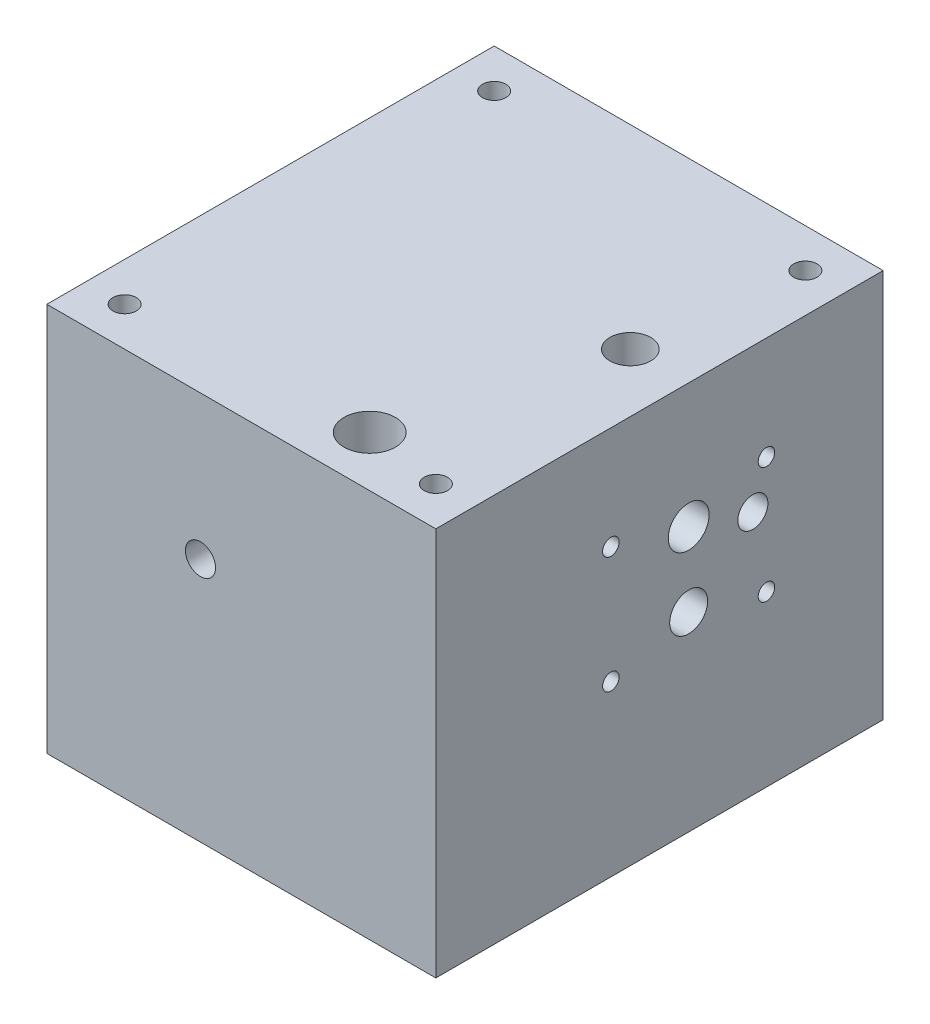
SolidWorks part; units mm, degrees
ref_plane "前视基准面" through (0, 0, 0) normal (0, 0, 1) x (1, 0, 0)
ref_plane "上视基准面" through (0, 0, 0) normal (0, 1, 0) x (1, 0, 0)
ref_plane "右视基准面" through (0, 0, 0) normal (1, 0, 0) x (0, 0, -1)
sketch "草图1" plane through (0, 0, 0) normal (0, 1, 0) x (1, 0, 0)
  line L1 (100, -100) -> (-100, -100)
  line L2 (100, -100) -> (100, 100)
  line L3 (100, 100) -> (-100, 100)
  line L4 (-100, -100) -> (-100, 100)
  line L5 (100, -100) -> (-100, 100) construction
  line L6 (100, 100) -> (-100, -100) construction
  point P0 (0, 0)
  dimension "D1" = 200
  dimension "D2" = 200
extrude "凸台-拉伸1" add sketch "草图1" along normal blind 200
sketch "草图9" plane through (100, 0, 0) normal (1, 0, 0) x (0, 0, -1)
  line L0 (0, 117) -> (0, 19.4773) construction
  line L1 (51, 74) -> (-51, 74)
  line L2 (51, 74) -> (51, 160)
  line L3 (51, 160) -> (-51, 160)
  line L4 (-51, 74) -> (-51, 160)
  line L5 (51, 74) -> (-51, 160) construction
  line L6 (51, 160) -> (-51, 74) construction
  line L7 (100, 200) -> (100, 0) construction
  line L8 (0, 117) -> (-57.0715, 117) construction
  line L9 (-100, 200) -> (100, 200) construction
  circle A0 centre (0, 136) radius 16.5
  circle A1 centre (0, 136) radius 16.5
  circle A2 centre (33, 126) radius 10
  circle A3 centre (0, 98) radius 16.5
  point P0 (-40, 147)
  point P1 (0, 117)
  point P2 (0, 117)
  point P7 (0, 136)
  point P8 (-40, 87)
  point P11 (0, 136)
  point P12 (40, 147)
  point P13 (40, 87)
  point P23 (33, 126)
  dimension "D14" = 33
  dimension "D15" = 33
  dimension "D19" = 20
  dimension "D21" = 33
  dimension "D1" = 86
  dimension "D2" = 102
  dimension "D3" = 100
  dimension "D4" = 40
  dimension "D5" = 40
  dimension "D6" = 30
  dimension "D7" = 30
  dimension "D8" = 30
  dimension "D9" = 30
  dimension "D10" = 11
  dimension "D11" = 40
  dimension "D12" = 19
  dimension "D13" = 19
  dimension "D16" = 40
  dimension "D17" = 9
  dimension "D18" = 33
  dimension "D20" = 38
hole_wizard "M10 螺纹孔1" positions "草图10" profile "草图11" tap size "M10" standard "GB"
sketch "草图10" plane through (100, 0, 0) normal (1, 0, 0) x (0, 0, -1)
  point P0 (-40, 87)
  point P3 (-40, 147)
  point P6 (40, 147)
  point P9 (40, 87)
sketch "草图11" plane through (100, 87, 40) normal (0, 1, 0) x (0, 0, -1)
  line L0 (0, 0) -> (0, 19.5537)
  line L1 (0, 19.5537) -> (4.25, 17)
  line L2 (4.25, 17) -> (4.25, 0)
  line L5 (4.25, 0) -> (0, 0)
  line L10 (0, 19.5537) -> (-4.25, 17) construction
  line L11 (0, -6.35) -> (0, 107.95) construction
  dimension "螺纹孔钻头直径" = 8.5
  dimension "螺纹孔钻头深度" = 17
  dimension "导头角度" = 118
cosmetic thread "孔螺蚊线5" parameters "D1"=17, "D2"=10
cosmetic thread "孔螺蚊线6" parameters "D1"=17, "D2"=10
cosmetic thread "孔螺蚊线7" parameters "D1"=17, "D2"=10
cosmetic thread "孔螺蚊线8" parameters "D1"=17, "D2"=10
sketch "草图12" plane through (0, 0, -100) normal (0, 0, -1) x (-1, 0, 0)
  line L0 (-100, 200) -> (-100, 0) construction
  line L1 (173, 43.5) -> (-173, 43.5)
  line L2 (173, 43.5) -> (173, 116.5)
  line L3 (173, 116.5) -> (-173, 116.5)
  line L4 (-173, 43.5) -> (-173, 116.5)
  line L5 (173, 43.5) -> (-173, 116.5) construction
  line L6 (173, 116.5) -> (-173, 43.5) construction
  line L7 (-68, 116.5) -> (-68, 43.5)
  line L8 (68, 116.5) -> (68, 43.5)
  line L9 (-100, 200) -> (100, 200) construction
  circle A0 centre (0, 62) radius 12.5
  circle A1 centre (0, 62) radius 9
  circle A2 centre (-21, 98) radius 9
  circle A3 centre (-21, 98) radius 12.5
  circle A4 centre (21, 98) radius 9
  circle A5 centre (21, 98) radius 12.5
  circle A6 centre (42, 62) radius 9
  circle A7 centre (42, 62) radius 12.5
  point P0 (0, 80)
  point P11 (44, 107)
  point P12 (21, 53)
  point P13 (-44, 107)
  point P14 (-21, 53)
  point P17 (0, 62)
  point P19 (-21, 98)
  point P22 (21, 98)
  point P31 (42, 62)
  dimension "D16" = 18
  dimension "D17" = 25
  dimension "D22" = 25
  dimension "D23" = 18
  dimension "D24" = 18
  dimension "D25" = 25
  dimension "D27" = 18
  dimension "D28" = 25
  dimension "D1" = 346
  dimension "D2" = 100
  dimension "D3" = 68
  dimension "D4" = 68
  dimension "D5" = 27
  dimension "D6" = 27
  dimension "D7" = 27
  dimension "D8" = 27
  dimension "D9" = 73
  dimension "D10" = 21
  dimension "D11" = 21
  dimension "D12" = 44
  dimension "D13" = 44
  dimension "D14" = 156.5
  dimension "D15" = 18
  dimension "D18" = 18
  dimension "D19" = 18
  dimension "D20" = 21
  dimension "D21" = 21
  dimension "D26" = 42
  dimension "D29" = 138
hole_wizard "M8 螺纹孔1" positions "草图13" profile "草图14" tap size "M8" standard "GB"
sketch "草图13" plane through (0, 0, -100) normal (0, 0, -1) x (-1, 0, 0)
  point P0 (-44, 107)
  point P3 (-21, 53)
  point P6 (21, 53)
  point P9 (44, 107)
sketch "草图14" plane through (44, 107, -100) normal (1, 0, 0) x (0, 1, 0)
  line L0 (0, 0) -> (0, 27.0429)
  line L1 (0, 27.0429) -> (3.4, 25)
  line L2 (3.4, 25) -> (3.4, 0)
  line L5 (3.4, 0) -> (0, 0)
  line L10 (0, 27.0429) -> (-3.4, 25) construction
  line L11 (0, -6.35) -> (0, 107.95) construction
  dimension "螺纹孔钻头直径" = 6.8
  dimension "螺纹孔钻头深度" = 25
  dimension "导头角度" = 118
cosmetic thread "孔螺蚊线9" parameters "D1"=16, "D2"=8
cosmetic thread "孔螺蚊线10" parameters "D1"=16, "D2"=8
cosmetic thread "孔螺蚊线11" parameters "D1"=16, "D2"=8
cosmetic thread "孔螺蚊线12" parameters "D1"=16, "D2"=8
sketch "草图16" plane through (-100, 0, 0) normal (-1, 0, 0) x (0, 0, 1)
  line L0 (-67.5744, 98.0404) -> (-50, 98.0404) construction
  line L5 (-50, 138) -> (56, 138)
  line L6 (-50, 138) -> (-50, 58)
  line L7 (-50, 58) -> (56, 58)
  line L8 (56, 138) -> (56, 58)
  line L9 (56, 98.0404) -> (97.1803, 98.0404) construction
  line L11 (-100, 200) -> (100, 200) construction
  circle A0 centre (0, 98.0404) radius 6
  circle A1 centre (0, 98.0404) radius 10
  circle A2 centre (-25, 98) radius 6
  circle A3 centre (-25, 98) radius 10
  point P4 (0, 98.0404)
  point P7 (23, 71.0404)
  point P8 (23, 125.0404)
  point P9 (-31, 125.0404)
  point P10 (-31, 71.0404)
  point P18 (-25, 98)
  dimension "D13" = 20
  dimension "D14" = 12
  dimension "D17" = 20
  dimension "D18" = 12
  dimension "D1" = 106
  dimension "D2" = 80
  dimension "D3" = 56
  dimension "D4" = 27
  dimension "D5" = 27
  dimension "D6" = 27
  dimension "D7" = 27
  dimension "D8" = 23
  dimension "D9" = 23
  dimension "D10" = 54
  dimension "D11" = 54
  dimension "D12" = 62
  dimension "D15" = 40
  dimension "D16" = 48
  dimension "D19" = 75
hole_wizard "M14 螺纹孔2" positions "草图19" profile "草图18" tap size "M14" standard "IS"
sketch "草图19" plane through (-100, 0, 0) normal (-1, 0, 0) x (0, 0, 1)
  point P0 (23, 125.0404)
  point P3 (-31, 125.0404)
  point P6 (-31, 71.0404)
  point P9 (23, 71.0404)
sketch "草图18" plane through (-100, 125.0404, 23) normal (0, 1, 0) x (0, 0, 1)
  line L0 (0, 0) -> (0, 20.6052)
  line L1 (0, 20.6052) -> (6, 17)
  line L2 (6, 17) -> (6, 0)
  line L5 (6, 0) -> (0, 0)
  line L10 (0, 20.6052) -> (-6, 17) construction
  line L11 (0, -6.35) -> (0, 107.95) construction
  dimension "螺纹孔钻头直径" = 12
  dimension "螺纹孔钻头深度" = 17
  dimension "导头角度" = 118
cosmetic thread "孔螺蚊线13" parameters "D1"=17, "D2"=14
cosmetic thread "孔螺蚊线14" parameters "D1"=17, "D2"=14
cosmetic thread "孔螺蚊线15" parameters "D1"=17, "D2"=14
cosmetic thread "孔螺蚊线16" parameters "D1"=17, "D2"=14
sketch "草图22" plane through (0, 200, 0) normal (0, 1, 0) x (1, 0, 0)
  line L0 (100, -100) -> (100, 100) construction
  line L1 (-173, 100) -> (173, 100) construction
  point P0 (70, 0)
  dimension "D1" = 30
  dimension "D2" = 100
hole_wizard "M24 螺纹孔的螺纹孔钻头1" positions "草图25" profile "草图26" hole size "M24" standard "IS"
sketch "草图25" plane through (0, 200, 0) normal (0, 1, 0) x (1, 0, 0)
  point P0 (70, 0)
sketch "草图26" plane through (70, 200, 0) normal (1, 0, 0) x (0, 0, 1)
  line L0 (0, 0) -> (0, 66.309)
  line L1 (0, 66.309) -> (10.5, 60)
  line L2 (10.5, 60) -> (10.5, 0)
  line L5 (10.5, 0) -> (0, 0)
  line L10 (0, 66.309) -> (-10.5, 60) construction
  line L11 (0, -6.35) -> (0, 107.95) construction
  dimension "孔直径" = 21
  dimension "孔深度" = 60
  dimension "导头角度" = 118
hole_wizard "M24 螺纹孔的螺纹孔钻头2" positions "草图29" profile "草图30" hole size "M24" standard "IS"
sketch "草图29" plane through (100, 0, 0) normal (1, 0, 0) x (0, 0, -1)
  point P0 (0, 136)
sketch "草图30" plane through (100, 136, 0) normal (0, 1, 0) x (0, 0, -1)
  line L0 (0, 0) -> (0, 48.309)
  line L1 (0, 48.309) -> (10.5, 42)
  line L2 (10.5, 42) -> (10.5, 0)
  line L5 (10.5, 0) -> (0, 0)
  line L10 (0, 48.309) -> (-10.5, 42) construction
  line L11 (0, -6.35) -> (0, 107.95) construction
  dimension "孔直径" = 21
  dimension "孔深度" = 42
  dimension "导头角度" = 118
hole_wizard "M22 螺纹孔的螺纹孔钻头1" positions "草图31" profile "草图32" hole size "M22" standard "IS"
sketch "草图31" plane through (0, 0, -100) normal (0, 0, -1) x (-1, 0, 0)
  point P0 (-21, 98)
sketch "草图32" plane through (21, 98, -100) normal (1, 0, 0) x (0, 1, 0)
  line L0 (0, 0) -> (0, 116.8584)
  line L1 (0, 116.8584) -> (9.75, 111)
  line L2 (9.75, 111) -> (9.75, 0)
  line L5 (9.75, 0) -> (0, 0)
  line L10 (0, 116.8584) -> (-9.75, 111) construction
  line L11 (0, -6.35) -> (0, 107.95) construction
  dimension "孔直径" = 19.5
  dimension "孔深度" = 111
  dimension "导头角度" = 118
hole_wizard "M22 螺纹孔的螺纹孔钻头3" positions "草图35" profile "草图36" hole size "M22" standard "IS"
sketch "草图35" plane through (-100, 0, 0) normal (-1, 0, 0) x (0, 0, 1)
  point P0 (-25, 98)
sketch "草图36" plane through (-100, 98, -25) normal (0, 1, 0) x (0, 0, 1)
  line L0 (0, 0) -> (0, 95.8584)
  line L1 (0, 95.8584) -> (9.75, 90)
  line L2 (9.75, 90) -> (9.75, 0)
  line L5 (9.75, 0) -> (0, 0)
  line L10 (0, 95.8584) -> (-9.75, 90) construction
  line L11 (0, -6.35) -> (0, 107.95) construction
  dimension "孔直径" = 19.5
  dimension "孔深度" = 90
  dimension "导头角度" = 118
hole_wizard "M22 螺纹孔的螺纹孔钻头4" positions "草图37" profile "草图38" hole size "M22" standard "IS"
sketch "草图37" plane through (0, 0, -100) normal (0, 0, -1) x (-1, 0, 0)
  point P0 (21, 98)
sketch "草图38" plane through (-21, 98, -100) normal (1, 0, 0) x (0, 1, 0)
  line L0 (0, 0) -> (0, 80.8584)
  line L1 (0, 80.8584) -> (9.75, 75)
  line L2 (9.75, 75) -> (9.75, 0)
  line L5 (9.75, 0) -> (0, 0)
  line L10 (0, 80.8584) -> (-9.75, 75) construction
  line L11 (0, -6.35) -> (0, 107.95) construction
  dimension "孔直径" = 19.5
  dimension "孔深度" = 75
  dimension "导头角度" = 118
hole_wizard "M18 螺纹孔的螺纹孔钻头1" positions "草图41" profile "草图42" hole size "M18" standard "GB"
sketch "草图41" plane through (-100, 0, 0) normal (-1, 0, 0) x (0, 0, 1)
  point P0 (0, 98.0404)
sketch "草图42" plane through (-100, 98.0404, 0) normal (0, 1, 0) x (0, 0, 1)
  line L0 (0, 0) -> (0, 92.6567)
  line L1 (0, 92.6567) -> (7.75, 88)
  line L2 (7.75, 88) -> (7.75, 0)
  line L5 (7.75, 0) -> (0, 0)
  line L10 (0, 92.6567) -> (-7.75, 88) construction
  line L11 (0, -6.35) -> (0, 107.95) construction
  dimension "孔直径" = 15.5
  dimension "孔深度" = 88
  dimension "导头角度" = 118
hole_wizard "M18 螺纹孔的螺纹孔钻头4" positions "草图48" profile "草图49" hole size "M18" standard "GB"
sketch "草图48" plane through (100, 0, 0) normal (1, 0, 0) x (0, 0, -1)
  point P0 (33, 126)
sketch "草图49" plane through (100, 126, -33) normal (0, 1, 0) x (0, 0, -1)
  line L0 (0, 0) -> (0, 134.6567)
  line L1 (0, 134.6567) -> (7.75, 130)
  line L2 (7.75, 130) -> (7.75, 0)
  line L5 (7.75, 0) -> (0, 0)
  line L10 (0, 134.6567) -> (-7.75, 130) construction
  line L11 (0, -6.35) -> (0, 107.95) construction
  dimension "孔直径" = 15.5
  dimension "孔深度" = 130
  dimension "导头角度" = 118
ref_plane "基准面2" through (0, 0, 0) normal (0, 0, 1) x (1, 0, 0)
sketch "草图50" plane through (0, 0, 0) normal (0, 0, 1) x (1, 0, 0)
  line L4 (-100, 0) -> (100, 0)
  line L5 (100, 0) -> (100, 200)
  line L6 (100, 200) -> (-100, 200)
  line L7 (-100, 200) -> (-100, 0)
  line L8 (-100, 0) -> (100, 0)
  line L9 (100, 0) -> (100, 200)
  line L10 (100, 200) -> (-100, 200)
  line L11 (-100, 200) -> (-100, 0)
  point P0 (-21, 126)
  dimension "D2" = 79
  dimension "D3" = 74
  dimension "D1" = 0
sketch "草图67" plane through (-100, 0, 0) normal (-1, 0, 0) x (0, 0, 1)
  line L0 (-100, 0) -> (100, 0) construction
  line L1 (19, 0) -> (-41, 0)
  line L2 (19, 0) -> (19, 53)
  line L3 (19, 53) -> (-41, 53)
  line L4 (-41, 0) -> (-41, 53)
  line L5 (-100, 200) -> (-100, 0) construction
  circle A0 centre (-25, 26.5) radius 5.5
  circle A1 centre (0, 26.5) radius 5.5
  point P6 (-9, 9)
  point P7 (-9, 44)
  point P8 (-29, 9)
  point P9 (-29, 44)
  point P10 (-25, 26.5)
  point P11 (0, 26.5)
  dimension "D14" = 11
  dimension "D15" = 11
  dimension "D1" = 60
  dimension "D2" = 53
  dimension "D3" = 12
  dimension "D4" = 32
  dimension "D5" = 12
  dimension "D6" = 32
  dimension "D7" = 9
  dimension "D8" = 9
  dimension "D9" = 9
  dimension "D10" = 9
  dimension "D11" = 26.5
  dimension "D12" = 16
  dimension "D13" = 100
  dimension "D16" = 75
hole_wizard "M22 螺纹孔的螺纹孔钻头5" positions "草图68" profile "草图69" hole size "M22" standard "GB"
sketch "草图68" plane through (100, 0, 0) normal (1, 0, 0) x (0, 0, -1)
  point P0 (0, 98)
sketch "草图69" plane through (100, 98, 0) normal (0, 1, 0) x (0, 0, -1)
  line L0 (0, 0) -> (0, 84.8584)
  line L1 (0, 84.8584) -> (9.75, 79)
  line L2 (9.75, 79) -> (9.75, 0)
  line L5 (9.75, 0) -> (0, 0)
  line L10 (0, 84.8584) -> (-9.75, 79) construction
  line L11 (0, -6.35) -> (0, 107.95) construction
  dimension "孔直径" = 19.5
  dimension "孔深度" = 79
  dimension "导头角度" = 118
hole_wizard "M10 螺纹孔2" positions "草图70" profile "草图71" tap size "M10" standard "GB"
sketch "草图70" plane through (-100, 0, 0) normal (-1, 0, 0) x (0, 0, 1)
  point P0 (-9, 44)
  point P3 (-29, 44)
  point P6 (-29, 9)
  point P9 (-9, 9)
sketch "草图71" plane through (-100, 44, -9) normal (0, 1, 0) x (0, 0, 1)
  line L0 (0, 0) -> (0, 12.5537)
  line L1 (0, 12.5537) -> (4.25, 10)
  line L2 (4.25, 10) -> (4.25, 0)
  line L5 (4.25, 0) -> (0, 0)
  line L10 (0, 12.5537) -> (-4.25, 10) construction
  line L11 (0, -6.35) -> (0, 107.95) construction
  dimension "螺纹孔钻头直径" = 8.5
  dimension "螺纹孔钻头深度" = 10
  dimension "导头角度" = 118
cosmetic thread "孔螺蚊线17" parameters "D1"=10, "D2"=10
cosmetic thread "孔螺蚊线18" parameters "D1"=10, "D2"=10
cosmetic thread "孔螺蚊线19" parameters "D1"=10, "D2"=10
cosmetic thread "孔螺蚊线20" parameters "D1"=10, "D2"=10
hole_wizard "M10 螺纹孔的螺纹孔钻头1" positions "草图72" profile "草图73" hole size "M10" standard "GB"
sketch "草图72" plane through (-100, 0, 0) normal (-1, 0, 0) x (0, 0, 1)
  point P0 (0, 26.5)
  point P3 (-25, 26.5)
sketch "草图73" plane through (-100, 26.5, 0) normal (0, 1, 0) x (0, 0, 1)
  line L0 (0, 0) -> (0, 42.5537)
  line L1 (0, 42.5537) -> (4.25, 40)
  line L2 (4.25, 40) -> (4.25, 0)
  line L5 (4.25, 0) -> (0, 0)
  line L10 (0, 42.5537) -> (-4.25, 40) construction
  line L11 (0, -6.35) -> (0, 107.95) construction
  dimension "孔直径" = 8.5
  dimension "孔深度" = 40
  dimension "导头角度" = 118
ref_plane "基准面3" through (0, 26.5, 0) normal (0, -1, 0) x (-1, 0, 0)
sketch "草图74" plane through (0, 26.5, 0) normal (0, -1, 0) x (-1, 0, 0)
  line L4 (100, -100) -> (100, 100)
  line L5 (100, 100) -> (-100, 100)
  line L6 (-100, 100) -> (-100, -100)
  line L7 (-100, -100) -> (100, -100)
  line L8 (100, -100) -> (100, 100)
  line L9 (100, 100) -> (-100, 100)
  line L10 (-100, 100) -> (-100, -100)
  line L11 (-100, -100) -> (100, -100)
  point P0 (64.25, 25)
  point P1 (64.25, 0)
  dimension "D2" = 35.75
  dimension "D3" = 35.75
  dimension "D4" = 100
  dimension "D5" = 75
  dimension "D1" = 0
hole_wizard "M10 螺纹孔的螺纹孔钻头2" positions "草图75" profile "草图76" hole size "M10" standard "GB"
sketch "草图75" plane through (0, 26.5, 0) normal (0, -1, 0) x (-1, 0, 0)
  point P0 (64.25, 0)
  point P3 (64.25, 25)
sketch "草图76" plane through (-64.25, 26.5, 0) normal (1, 0, 0) x (0, 0, -1)
  line L0 (0, 0) -> (0, 74.0537)
  line L1 (0, 74.0537) -> (4.25, 71.5)
  line L2 (4.25, 71.5) -> (4.25, 0)
  line L5 (4.25, 0) -> (0, 0)
  line L10 (0, 74.0537) -> (-4.25, 71.5) construction
  line L11 (0, -6.35) -> (0, 107.95) construction
  dimension "孔直径" = 8.5
  dimension "孔深度" = 71.5
  dimension "导头角度" = 118
hole_wizard "M24 螺纹孔的螺纹孔钻头3" positions "草图77" profile "草图78" hole size "M24" standard "GB"
sketch "草图77" plane through (0, 0, -100) normal (0, 0, -1) x (-1, 0, 0)
  point P0 (0, 62)
sketch "草图78" plane through (0, 62, -100) normal (1, 0, 0) x (0, 1, 0)
  line L0 (0, 0) -> (0, 46.809)
  line L1 (0, 46.809) -> (10.5, 40.5)
  line L2 (10.5, 40.5) -> (10.5, 0)
  line L5 (10.5, 0) -> (0, 0)
  line L10 (0, 46.809) -> (-10.5, 40.5) construction
  line L11 (0, -6.35) -> (0, 107.95) construction
  dimension "孔直径" = 21
  dimension "孔深度" = 40.5
  dimension "导头角度" = 118
sketch "草图79" plane through (0, 0, 0) normal (0, -1, 0) x (1, 0, 0)
  line L0 (100, 100) -> (100, -100) construction
  line L1 (100, -100) -> (-100, -100) construction
  point P0 (0, -70)
  dimension "D1" = 100
  dimension "D2" = 30
hole_wizard "M24 螺纹孔的螺纹孔钻头4" positions "草图80" profile "草图81" hole size "M24" standard "GB"
sketch "草图80" plane through (0, 0, 0) normal (0, -1, 0) x (-1, 0, 0)
  point P0 (0, 70)
sketch "草图81" plane through (0, 0, -70) normal (1, 0, 0) x (0, 0, -1)
  line L0 (0, 0) -> (0, 68.309)
  line L1 (0, 68.309) -> (10.5, 62)
  line L2 (10.5, 62) -> (10.5, 0)
  line L5 (10.5, 0) -> (0, 0)
  line L10 (0, 68.309) -> (-10.5, 62) construction
  line L11 (0, -6.35) -> (0, 107.95) construction
  dimension "孔直径" = 21
  dimension "孔深度" = 62
  dimension "导头角度" = 118
sketch "草图82" plane through (0, 0, 100) normal (0, 0, 1) x (1, 0, 0)
  line L0 (-100, 200) -> (100, 200) construction
  line L1 (-100, 200) -> (-100, 0) construction
  point P0 (-21, 126)
  dimension "D1" = 74
  dimension "D2" = 79
hole_wizard "M18 螺纹孔的螺纹孔钻头5" positions "草图83" profile "草图84" hole size "M18" standard "GB"
sketch "草图83" plane through (0, 0, 100) normal (0, 0, 1) x (1, 0, 0)
  point P0 (-21, 126)
sketch "草图84" plane through (-21, 126, 100) normal (1, 0, 0) x (0, -1, 0)
  line L0 (0, 0) -> (0, 137.6567)
  line L1 (0, 137.6567) -> (7.75, 133)
  line L2 (7.75, 133) -> (7.75, 0)
  line L5 (7.75, 0) -> (0, 0)
  line L10 (0, 137.6567) -> (-7.75, 133) construction
  line L11 (0, -6.35) -> (0, 107.95) construction
  dimension "孔直径" = 15.5
  dimension "孔深度" = 133
  dimension "导头角度" = 118
ref_plane "基准面4" through (0, 100, 0) normal (0, 1, 0) x (1, 0, 0)
sketch "草图85" plane through (0, 100, 0) normal (0, 1, 0) x (1, 0, 0)
  line L0 (-100, -19) -> (-100, 41) construction
  line L1 (-100, -100) -> (100, -100) construction
  point P0 (-21, 0)
  dimension "D1" = 79
  dimension "D2" = 100
hole_wizard "M18 螺纹孔的螺纹孔钻头6" positions "草图89" profile "草图90" hole size "M18" standard "GB"
sketch "草图89" plane through (0, 100, 0) normal (0, 1, 0) x (1, 0, 0)
  point P0 (-21, 0)
sketch "草图90" plane through (-21, 100, 0) normal (1, 0, 0) x (0, 0, -1)
  line L0 (0, 0) -> (0, 32.6567)
  line L1 (0, 32.6567) -> (7.75, 28)
  line L2 (7.75, 28) -> (7.75, 0)
  line L5 (7.75, 0) -> (0, 0)
  line L10 (0, 32.6567) -> (-7.75, 28) construction
  line L11 (0, -6.35) -> (0, 107.95) construction
  dimension "孔直径" = 15.5
  dimension "孔深度" = 28
  dimension "导头角度" = 118
hole_wizard "M18 螺纹孔的螺纹孔钻头7" positions "草图93" profile "草图94" hole size "M18" standard "GB"
sketch "草图93" plane through (0, 0, -100) normal (0, 0, -1) x (-1, 0, 0)
  point P0 (42, 62)
sketch "草图94" plane through (-42, 62, -100) normal (1, 0, 0) x (0, 1, 0)
  line L0 (0, 0) -> (0, 112.3567)
  line L1 (0, 112.3567) -> (7.75, 107.7)
  line L2 (7.75, 107.7) -> (7.75, 0)
  line L5 (7.75, 0) -> (0, 0)
  line L10 (0, 112.3567) -> (-7.75, 107.7) construction
  line L11 (0, -6.35) -> (0, 107.95) construction
  dimension "孔直径" = 15.5
  dimension "孔深度" = 107.7
  dimension "导头角度" = 118
ref_plane "基准面5" through (0, 62, 0) normal (0, -1, 0) x (-1, 0, 0)
sketch "草图96" plane through (0, 62, 0) normal (0, -1, 0) x (-1, 0, 0)
  line L0 (-100, 100) -> (100, 100) construction
  line L1 (100, 100) -> (100, -100) construction
  point P0 (42, 0)
  dimension "D1" = 100
  dimension "D2" = 58
hole_wizard "M18 螺纹孔的螺纹孔钻头8" positions "草图99" profile "草图100" hole size "M18" standard "GB"
sketch "草图99" plane through (0, 62, 0) normal (0, -1, 0) x (-1, 0, 0)
  point P0 (42, 0)
sketch "草图100" plane through (-42, 62, 0) normal (1, 0, 0) x (0, 0, -1)
  line L0 (0, 0) -> (0, 40.6567)
  line L1 (0, 40.6567) -> (7.75, 36)
  line L2 (7.75, 36) -> (7.75, 0)
  line L5 (7.75, 0) -> (0, 0)
  line L10 (0, 40.6567) -> (-7.75, 36) construction
  line L11 (0, -6.35) -> (0, 107.95) construction
  dimension "孔直径" = 15.5
  dimension "孔深度" = 36
  dimension "导头角度" = 118
sketch "草图101" plane through (0, 0, -100) normal (0, 0, -1) x (-1, 0, 0)
  point P0 (189.0213, 186.0801)
sketch "草图102" plane through (0, 0, -100) normal (0, 0, -1) x (-1, 0, 0)
  point P0 (-21, 160)
hole_wizard "M22 螺纹孔的螺纹孔钻头6" positions "草图105" profile "草图106" hole size "M22" standard "GB"
sketch "草图105" plane through (0, 0, -100) normal (0, 0, -1) x (-1, 0, 0)
  point P0 (-21, 160)
sketch "草图106" plane through (21, 160, -100) normal (1, 0, 0) x (0, 1, 0)
  line L0 (0, 0) -> (0, 45.6084)
  line L1 (0, 45.6084) -> (9.75, 39.75)
  line L2 (9.75, 39.75) -> (9.75, 0)
  line L5 (9.75, 0) -> (0, 0)
  line L10 (0, 45.6084) -> (-9.75, 39.75) construction
  line L11 (0, -6.35) -> (0, 107.95) construction
  dimension "孔直径" = 19.5
  dimension "孔深度" = 39.75
  dimension "导头角度" = 118
ref_plane "基准面6" through (0, 160, 0) normal (0, 1, 0) x (1, 0, 0)
sketch "草图107" plane through (0, 160, 0) normal (0, 1, 0) x (1, 0, 0)
  line L0 (-173, 100) -> (173, 100) construction
  point P0 (21, 70)
  dimension "D1" = 30
hole_wizard "M22 螺纹孔的螺纹孔钻头7" positions "草图108" profile "草图109" hole size "M22" standard "GB"
sketch "草图108" plane through (0, 160, 0) normal (0, 1, 0) x (1, 0, 0)
  point P0 (21, 70)
sketch "草图109" plane through (21, 160, -70) normal (1, 0, 0) x (0, 0, 1)
  line L0 (0, 0) -> (0, 67.8584)
  line L1 (0, 67.8584) -> (9.75, 62)
  line L2 (9.75, 62) -> (9.75, 0)
  line L5 (9.75, 0) -> (0, 0)
  line L10 (0, 67.8584) -> (-9.75, 62) construction
  line L11 (0, -6.35) -> (0, 107.95) construction
  dimension "孔直径" = 19.5
  dimension "孔深度" = 62
  dimension "导头角度" = 118
sketch "草图110" plane through (0, 0, 100) normal (0, 0, 1) x (1, 0, 0)
  line L4 (-100, 0) -> (100, 0)
  line L5 (100, 0) -> (100, 200)
  line L6 (100, 200) -> (-100, 200)
  line L7 (-100, 200) -> (-100, 0)
  line L8 (-100, 0) -> (100, 0)
  line L9 (100, 0) -> (100, 200)
  line L10 (100, 200) -> (-100, 200)
  line L11 (-100, 200) -> (-100, 0)
  dimension "D1" = 0
extrude "凸台-拉伸2" add sketch "草图110" along normal blind 30
sketch "草图111" plane through (0, 0, 0) normal (0, -1, 0) x (1, 0, 0)
  line L0 (100, 130) -> (100, -100) construction
  line L1 (-100, 130) -> (100, 130) construction
  line L2 (100, -100) -> (-100, -100) construction
  line L3 (-100, -100) -> (-100, 130) construction
  point P0 (80, 110)
  point P1 (-80, 110)
  point P2 (-80, -80)
  point P3 (80, -80)
  dimension "D1" = 20
  dimension "D2" = 20
  dimension "D3" = 20
  dimension "D4" = 20
  dimension "D5" = 20
  dimension "D6" = 20
  dimension "D7" = 20
  dimension "D8" = 20
hole_wizard "M14 螺纹孔的螺纹孔钻头2" positions "草图112" profile "草图113" hole size "M14" standard "GB" end condition through all
sketch "草图112" plane through (0, 0, 0) normal (0, -1, 0) x (-1, 0, 0)
  point P0 (-80, -110)
  point P3 (80, -110)
  point P6 (80, 80)
  point P9 (-80, 80)
sketch "草图113" plane through (80, 0, 110) normal (1, 0, 0) x (0, 0, -1)
  line L0 (0, 0) -> (0, 200)
  line L1 (0, 200) -> (6, 200)
  line L2 (6, 200) -> (6, 0)
  line L5 (6, 0) -> (0, 0)
  line L11 (0, -6.35) -> (0, 107.95) construction
  dimension "通孔孔直径" = 12
  dimension "通孔孔深度" = 200
sketch "草图114" plane through (0, 0, 130) normal (0, 0, 1) x (1, 0, 0)
  circle A0 centre (-21, 126) radius 7.75 construction
  circle A1 centre (-21, 126) radius 7.75
  point P1 (-173.9605, 299.4887)
  point P6 (-21, 126)
hole_wizard "M18 螺纹孔的螺纹孔钻头9" positions "草图115" profile "草图116" hole size "M18" standard "GB"
sketch "草图115" plane through (0, 0, 130) normal (0, 0, 1) x (1, 0, 0)
  point P0 (-21, 126)
sketch "草图116" plane through (-21, 126, 130) normal (1, 0, 0) x (0, -1, 0)
  line L0 (0, 0) -> (0, 66.6567)
  line L1 (0, 66.6567) -> (7.75, 62)
  line L2 (7.75, 62) -> (7.75, 0)
  line L5 (7.75, 0) -> (0, 0)
  line L10 (0, 66.6567) -> (-7.75, 62) construction
  line L11 (0, -6.35) -> (0, 107.95) construction
  dimension "孔直径" = 15.5
  dimension "孔深度" = 62
  dimension "导头角度" = 118
sketch "草图117" plane through (0, 0, 0) normal (0, -1, 0) x (1, 0, 0)
  line L0 (100, 130) -> (100, -100) construction
  line L1 (-100, 130) -> (100, 130) construction
  point P0 (40, 104)
  dimension "D1" = 60
  dimension "D2" = 26
hole_wizard "M30 螺纹孔的螺纹孔钻头1" positions "草图122" profile "草图123" hole size "M30" standard "GB" end condition through all
sketch "草图122" plane through (0, 0, 0) normal (0, -1, 0) x (-1, 0, 0)
  point P0 (-40, -104)
sketch "草图123" plane through (40, 0, 104) normal (1, 0, 0) x (0, 0, -1)
  line L0 (0, 0) -> (0, 200)
  line L1 (0, 200) -> (13.25, 200)
  line L2 (13.25, 200) -> (13.25, 0)
  line L5 (13.25, 0) -> (0, 0)
  line L11 (0, -6.35) -> (0, 107.95) construction
  dimension "通孔孔直径" = 26.5
  dimension "通孔孔深度" = 200
